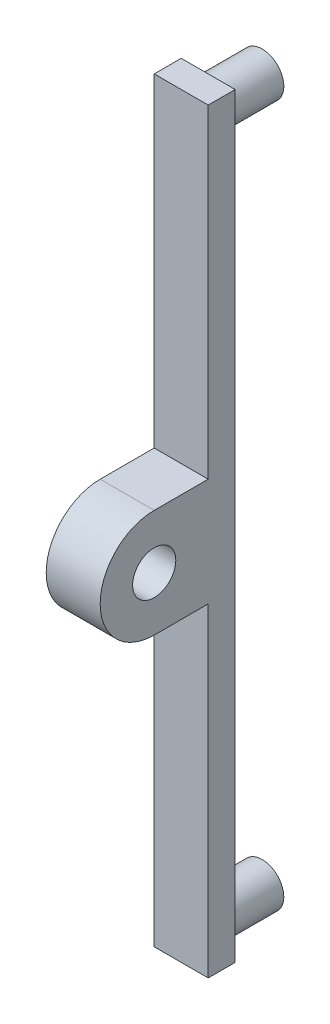
SolidWorks part; units mm, degrees
ref_plane "Front Plane" through (0, 0, 0) normal (0, 0, 1) x (1, 0, 0)
ref_plane "Top Plane" through (0, 0, 0) normal (0, 1, 0) x (1, 0, 0)
ref_plane "Right Plane" through (0, 0, 0) normal (1, 0, 0) x (0, 0, -1)
sketch "Sketch1" plane through (0, 0, 0) normal (1, 0, 0) x (0, 0, -1)
  line L0 (10, 70) -> (10, 10)
  line L1 (0, 0) -> (4, 0) construction
  line L2 (15, 70) -> (15, -70)
  line L3 (10, 70) -> (15, 70)
  line L4 (10, -70) -> (15, -70)
  line L5 (0, 10) -> (10, 10)
  line L6 (0, -10) -> (10, -10)
  line L7 (15, 0) -> (64.3819, 0) construction
  line L8 (10, -10) -> (10, -70)
  line L9 (10, 70) -> (10, -70) construction
  circle A0 centre (0, 0) radius 4
  arc A1 (0, 10) -> (0, -10) centre (0, 0) ccw
  point P8 (10, 0)
  dimension "D1" = 8
  dimension "D2" = 20
  dimension "D3" = 70
  dimension "D4" = 5
extrude "Boss-Extrude1" add sketch "Sketch1" along normal blind 10
sketch "Sketch2" plane through (0, 0, -15) normal (0, 0, -1) x (-1, 0, 0)
  line L2 (-10, 70) -> (0, 70) construction
  line L3 (-10, 70) -> (-10, -70) construction
  line L4 (0, 0) -> (-46.1159, 0) construction
  circle A0 centre (-5, 65) radius 4
  circle A1 centre (-5, -65) radius 4
  dimension "D1" = 8
  dimension "D2" = 5
  dimension "D3" = 5
extrude "Boss-Extrude2" add sketch "Sketch2" along normal blind 10
